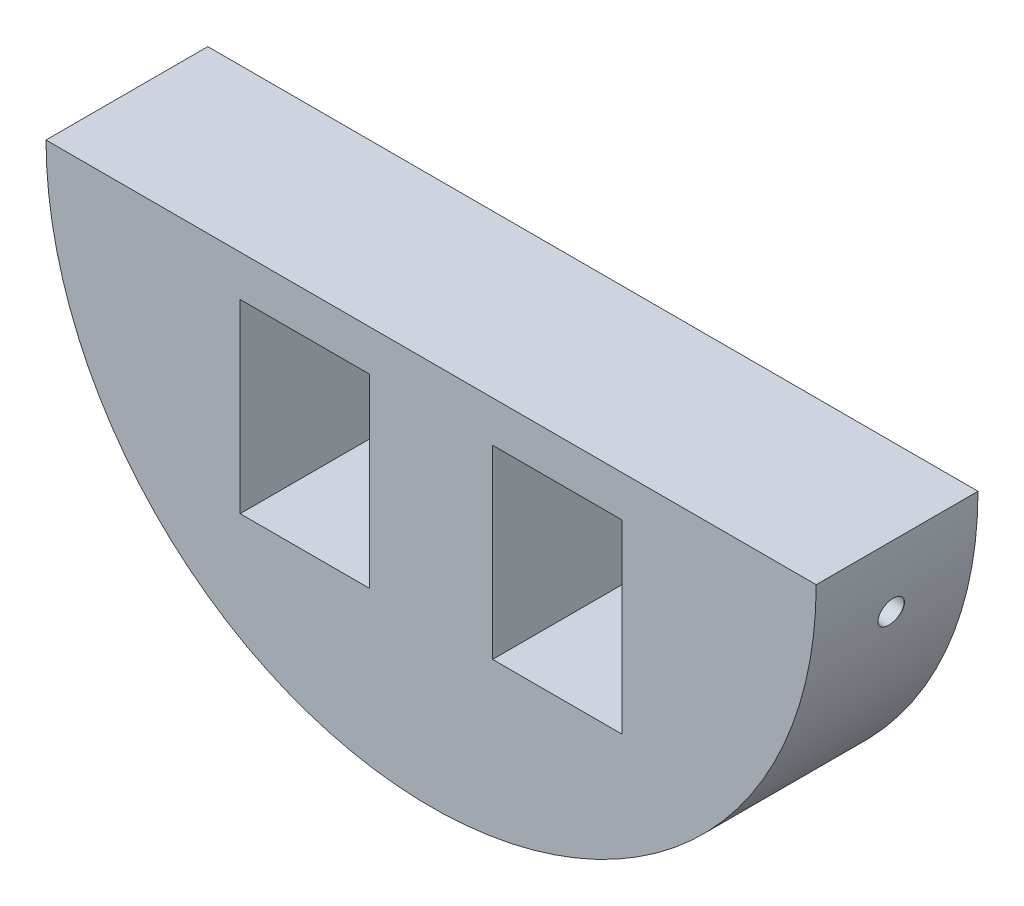
SolidWorks part; units mm, degrees
ref_plane "Front Plane" through (0, 0, 0) normal (0, 0, 1) x (1, 0, 0)
ref_plane "Top Plane" through (0, 0, 0) normal (0, 1, 0) x (1, 0, 0)
ref_plane "Right Plane" through (0, 0, 0) normal (1, 0, 0) x (0, 0, -1)
sketch "Sketch1" plane through (0, 0, 0) normal (0, 0, 1) x (1, 0, 0)
  line L0 (-119, 0) -> (0, 0)
  line L3 (-50, -35) -> (-30, -35)
  line L4 (-50, -35) -> (-50, -15)
  line L5 (-50, -15) -> (-30, -15)
  line L6 (-30, -35) -> (-30, -15)
  line L7 (-89, -35) -> (-69, -35)
  line L8 (-89, -35) -> (-89, -15)
  line L9 (-89, -15) -> (-69, -15)
  line L10 (-69, -35) -> (-69, -15)
  arc A1 (-119, 0) -> (0, 0) centre (-59.5, 0) ccw
  dimension "D1" = 30
  dimension "D7" = 59.5
  dimension "D2" = 15
  dimension "D3" = 30
  dimension "D4" = 20
extrude "Boss-Extrude1" add sketch "Sketch1" along normal blind 25
hole_wizard "Ø4.0mm Dowel Hole2" positions "3DSketch2" profile "Sketch4" hole size "Ø4.0" standard "ANSI Metric"
sketch3d "3DSketch2"
  line L2 (0, 0, 25) -> (0, 0, 0) construction
  line L4 (0, 0, 25) -> (0, 0, 0) construction
  line L5 (0, 0, 12.5) -> (-0.9039, -10.3321, 12.5) construction
  line L8 (-59.5, 0, 0) -> (-59.5, 0, 25) construction
  line L9 (0, 0, 0) -> (-119, 0, 0) construction
  line L10 (0, 0, 25) -> (-119, 0, 25) construction
  line L12 (-59.5, 0, 12.5) -> (-0.9039, -10.3321, 12.5) construction
  line L16 (-59.5, 0, 12.5) -> (0, 0, 12.5) construction
  point P0 (-0.9039, -10.3321, 12.5)
  point P16 (-0.9039, -10.3321, 12.5)
  point P23 (-0.9039, -10.3321, 12.5)
  point P25 (-0.9039, -10.3321, 12.5)
  dimension "D1" = 10
sketch "Sketch4" plane through (-0.9039, -10.3321, 12.5) normal (0, 0, 1) x (0.1736, 0.9848, 0)
  line L0 (0, 0) -> (0, 11.2017)
  line L1 (0, 11.2017) -> (2, 10)
  line L2 (2, 10) -> (2, 0.025)
  line L3 (2, 0.025) -> (2.025, 0)
  line L5 (2.025, 0) -> (0, 0)
  line L6 (-2, 0.025) -> (-2.025, 0) construction
  line L10 (0, 11.2017) -> (-2, 10) construction
  line L11 (0, -6.35) -> (0, 107.95) construction
  dimension "Hole Dia." = 4
  dimension "Hole Depth" = 10
  dimension "Near C'Sink Dia." = 4.05
  dimension "Near C'Sink Angle" = 90
  dimension "Drill Angle" = 118
pattern_circular "CirPattern1" count 5 over 160 about axis through (-59.5, 0, 0) along (0, 0, 1) of "Ø4.0mm Dowel Hole2"
chamfer "Chamfer1" distance 15 angle 30 2 edges at (-79, -15, 25) (-40, -15, 25)
